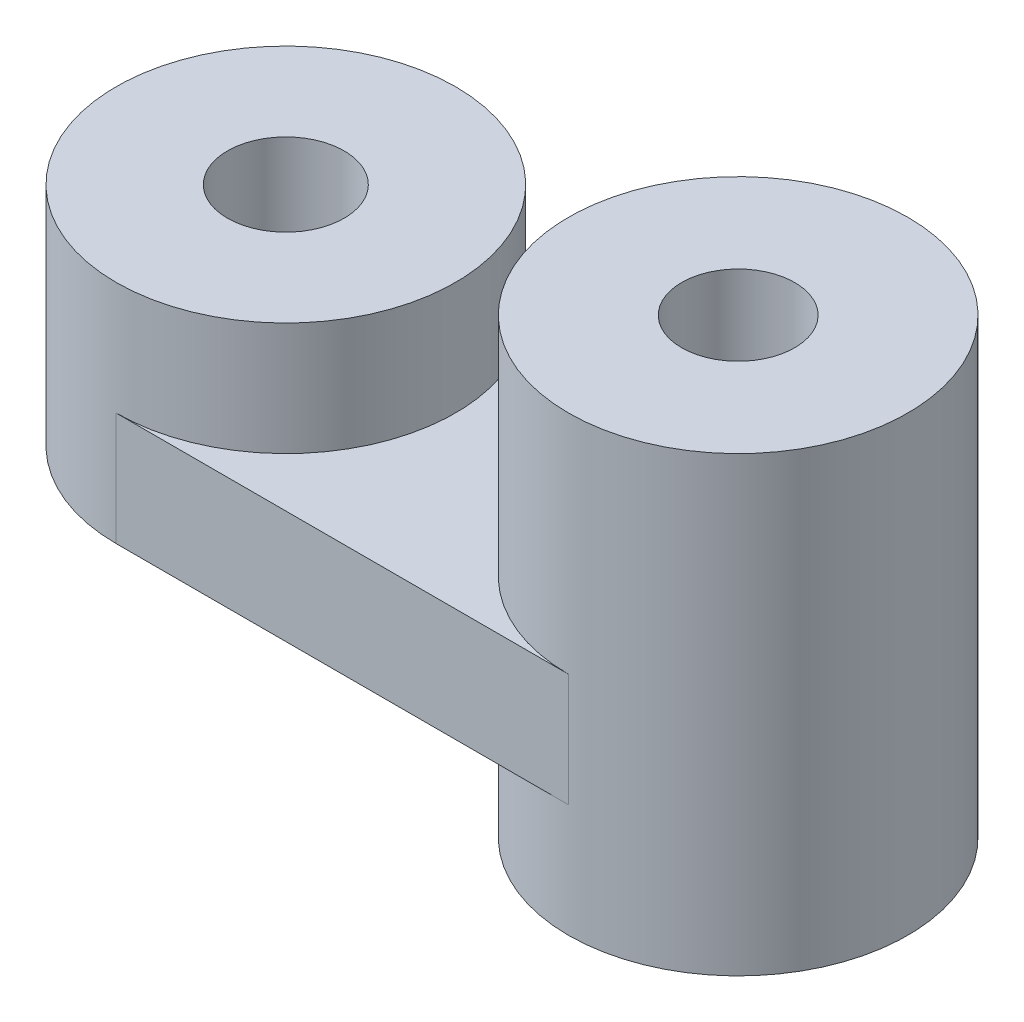
SolidWorks part; units mm, degrees
ref_plane "Alzado" through (0, 0, 0) normal (0, 0, 1) x (1, 0, 0)
ref_plane "Planta" through (0, 0, 0) normal (0, 1, 0) x (1, 0, 0)
ref_plane "Vista lateral" through (0, 0, 0) normal (1, 0, 0) x (0, 0, -1)
sketch "Croquis1" plane through (0, 0, 0) normal (0, 1, 0) x (1, 0, 0)
  line L0 (-10, 0) -> (10, 0) construction
  line L1 (-10, 7.5) -> (10, 7.5)
  line L2 (-10, -7.5) -> (10, -7.5)
  circle A0 centre (-10, 0) radius 2.5
  circle A1 centre (10, 0) radius 2.5
  circle A2 centre (10, 0) radius 7.5
  circle A3 centre (-10, 0) radius 7.5
  point P4 (0, 0)
  point P12 (17.5, 7.5)
  dimension "D1" = 15
  dimension "D2" = 5
  dimension "D3" = 5
  dimension "D4" = 15
  dimension "D5" = 20
extrude "Saliente-Extruir1" add sketch "Croquis1" along normal blind 5
sketch "Croquis2" plane through (0, 5, 0) normal (0, 1, 0) x (1, 0, 0)
  circle A0 centre (-10, 0) radius 2.5808
  circle A1 centre (-10, 0) radius 7.5
  point P4 (0, 0)
extrude "Saliente-Extruir2" add sketch "Croquis2" along normal blind 5
sketch "Croquis3" plane through (0, 5, 0) normal (0, 1, 0) x (1, 0, 0)
  circle A0 centre (10, 0) radius 2.5
  circle A1 centre (10, 0) radius 7.5
extrude "Saliente-Extruir3" add sketch "Croquis3" along normal blind 10 and the other way blind 10
